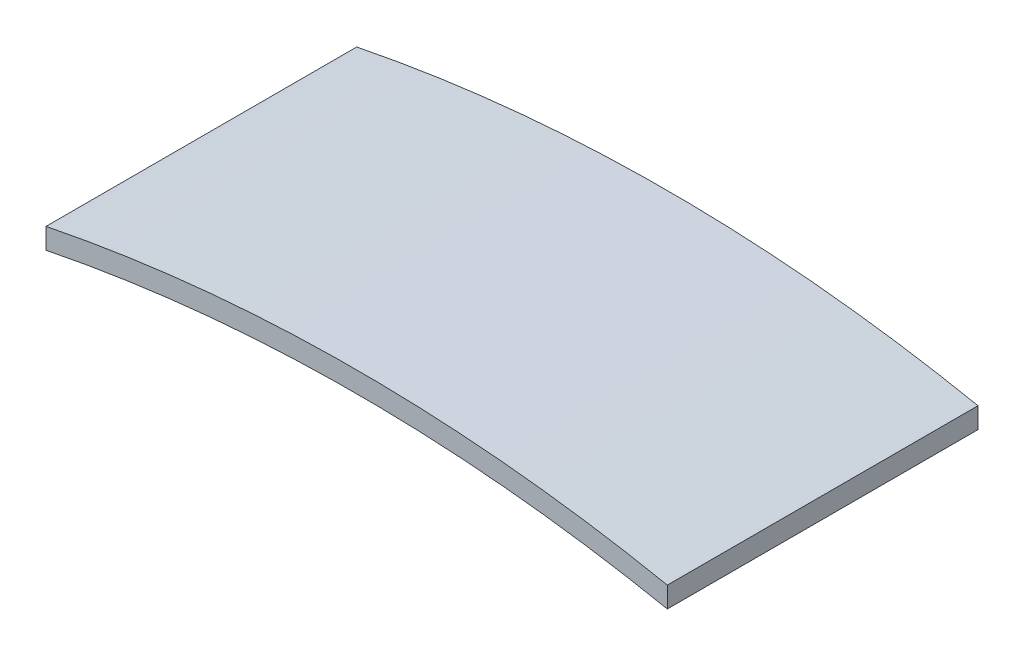
SolidWorks part; units mm, degrees
ref_plane "前视基准面" through (0, 0, 0) normal (0, 0, 1) x (1, 0, 0)
ref_plane "上视基准面" through (0, 0, 0) normal (0, 1, 0) x (1, 0, 0)
ref_plane "右视基准面" through (0, 0, 0) normal (1, 0, 0) x (0, 0, -1)
other "Configuration Table"
sketch "草图1" plane through (0, 0, 0) normal (0, 0, 1) x (1, 0, 0)
  line L0 (150, 115) -> (150, 125)
  line L1 (-150, 125) -> (-150, 115)
  arc A0 (-150, 115) -> (150, 115) centre (0, -627.5) cw
  arc A1 (150, 125) -> (-150, 125) centre (0, -617.5) ccw
extrude "TEST_L300_W150_RISE15_VERTICAL_T10" add sketch "草图1" along normal blind 150
